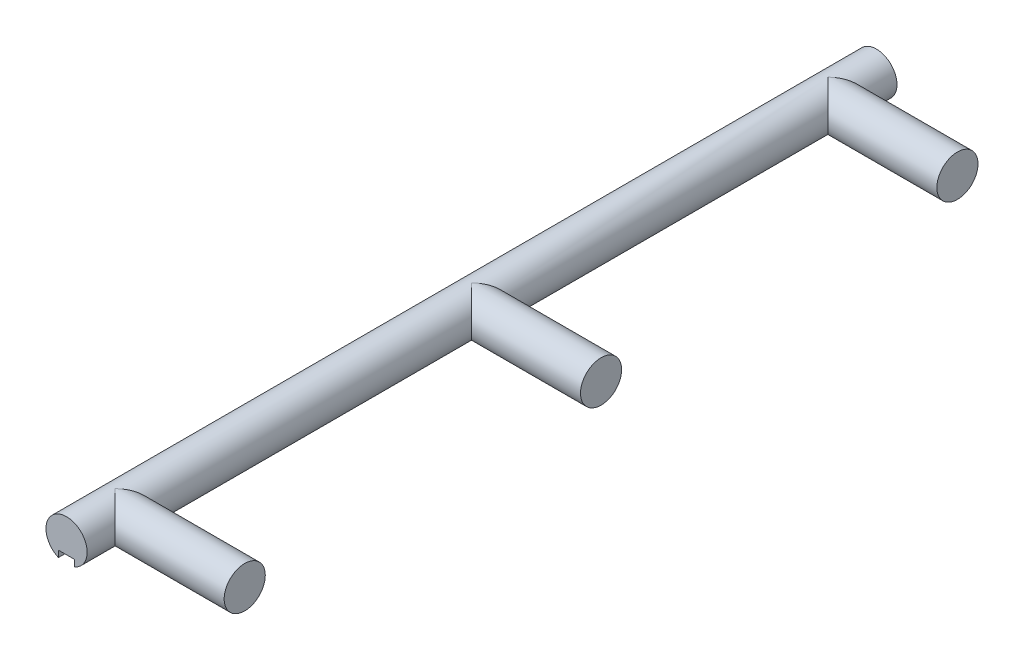
SolidWorks part; units mm, degrees
ref_plane "Alzado" through (0, 0, 0) normal (0, 0, 1) x (1, 0, 0)
ref_plane "Planta" through (0, 0, 0) normal (0, 1, 0) x (1, 0, 0)
ref_plane "Vista lateral" through (0, 0, 0) normal (1, 0, 0) x (0, 0, -1)
sketch "Croquis1" plane through (0, 0, 0) normal (0, 0, 1) x (1, 0, 0)
  circle A0 centre (0, 0) radius 6.35
  dimension "D1" = 12.7
extrude "Saliente-Extruir1" add sketch "Croquis1" along normal mid plane 250
sketch "Croquis2" plane through (0, 0, 0) normal (1, 0, 0) x (0, 0, -1)
  circle A0 centre (0, 0) radius 6.35
  circle A1 centre (110, 0) radius 6.35
  circle A2 centre (-110, 0) radius 6.35
  dimension "D1" = 12.7
  dimension "D2" = 2
  dimension "D3" = 2
extrude "Saliente-Extruir2" add sketch "Croquis2" along normal blind 40
sketch "Croquis3" plane through (0, 0, 125) normal (0, 0, 1) x (1, 0, 0)
  line L1 (2.5, -8.85) -> (-2.5, -8.85)
  line L2 (2.5, -8.85) -> (2.5, -3.85)
  line L3 (2.5, -3.85) -> (-2.5, -3.85)
  line L4 (-2.5, -8.85) -> (-2.5, -3.85)
  line L5 (2.5, -8.85) -> (-2.5, -3.85) construction
  line L6 (2.5, -3.85) -> (-2.5, -8.85) construction
  circle A1 centre (0, 0) radius 6.35 construction
  point P0 (0, -6.35)
  dimension "D1" = 5
  dimension "D2" = 5
extrude "Cortar-Extruir1" cut sketch "Croquis3" against normal blind 20
